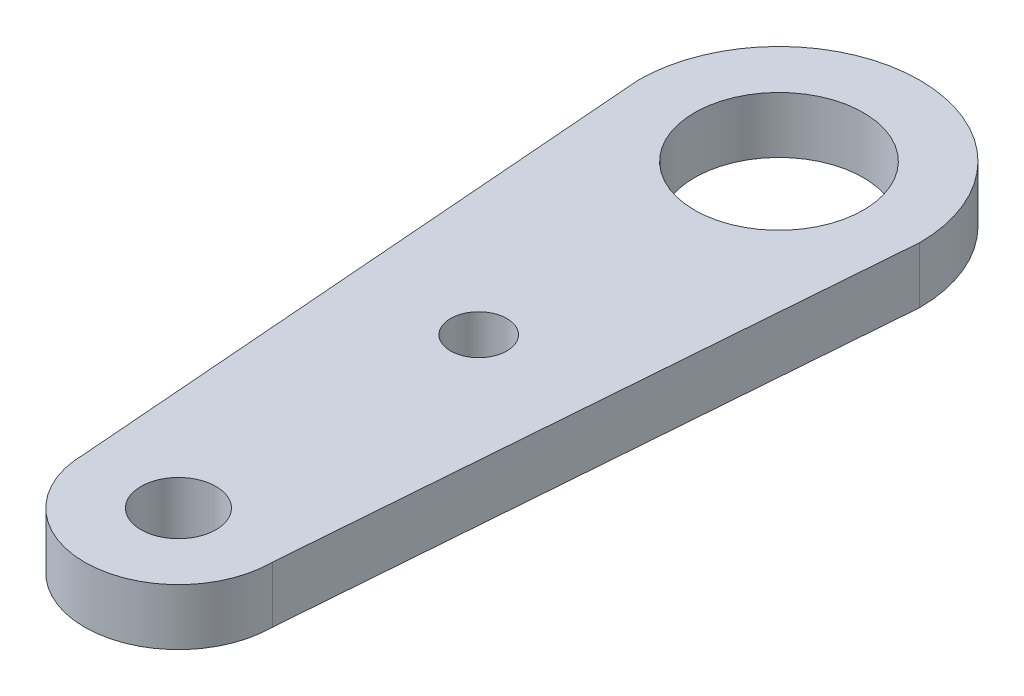
SolidWorks part; units mm, degrees
material "Thornel Mat VMA"
ref_plane "前视基准面" through (0, 0, 0) normal (0, 0, 1) x (1, 0, 0)
ref_plane "上视基准面" through (0, 0, 0) normal (0, 1, 0) x (1, 0, 0)
ref_plane "右视基准面" through (0, 0, 0) normal (1, 0, 0) x (0, 0, -1)
sketch "草图1" plane through (0, 0, 0) normal (0, 1, 0) x (1, 0, 0)
  line L0 (-7.5, 32) -> (-5, 0)
  line L1 (7.5, 32) -> (5, 0)
  circle A0 centre (0, 0) radius 2
  circle A1 centre (0, 32) radius 7.5
  circle A2 centre (0, 32) radius 4.5
  circle A3 centre (0, 0) radius 5
  dimension "D1" = 4
  dimension "D2" = 15
  dimension "D4" = 9
  dimension "D5" = 10
  dimension "D3" = 32
extrude "凸台-拉伸1" add sketch "草图1" along normal blind 3 contours L1 A1 L0 A2 | A3 A0 | A3 L1 A1 L0
sketch "草图2" plane through (0, 3, 0) normal (0, 1, 0) x (1, 0, 0)
  line L0 (0, 32) -> (0, 0) construction
  circle A0 centre (0, 16) radius 1.5
  dimension "D1" = 3
extrude "切除-拉伸1" cut sketch "草图2" against normal through all
